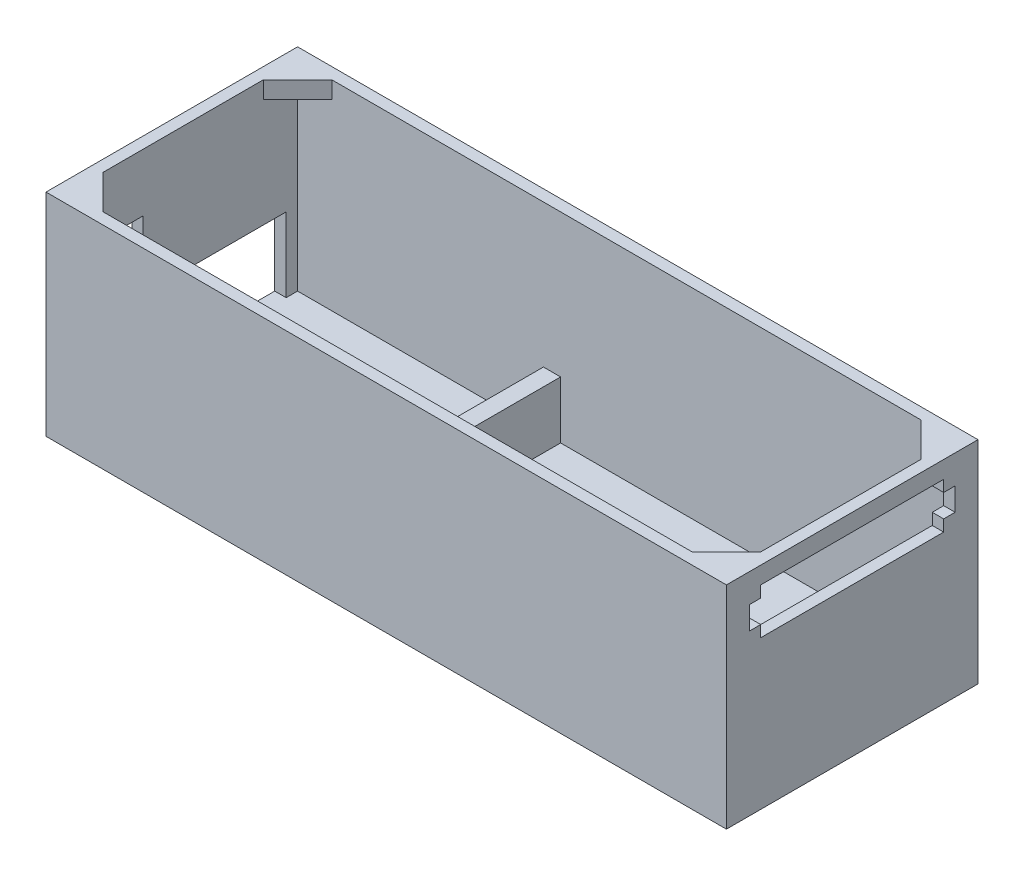
SolidWorks part; units mm, degrees
ref_plane "Plano frontal" through (0, 0, 0) normal (0, 0, 1) x (1, 0, 0)
ref_plane "Plano superior" through (0, 0, 0) normal (0, 1, 0) x (1, 0, 0)
ref_plane "Plano direito" through (0, 0, 0) normal (1, 0, 0) x (0, 0, -1)
sketch "Esboço1" plane through (0, 0, 0) normal (0, 1, 0) x (1, 0, 0)
  line L1 (-59.5, 22) -> (59.5, 22)
  line L2 (-59.5, 22) -> (-59.5, -22)
  line L3 (-59.5, -22) -> (59.5, -22)
  line L4 (59.5, 22) -> (59.5, -22)
  line L5 (-59.5, 22) -> (59.5, -22) construction
  line L6 (-59.5, -22) -> (59.5, 22) construction
  point P0 (0, 0)
  dimension "D1" = 44
  dimension "D2" = 119
extrude "Ressalto-extrusão2" add sketch "Esboço1" along normal blind 2
sketch "Esboço2" plane through (0, 2, 0) normal (0, 1, 0) x (1, 0, 0)
  line L1 (-59.5, -22) -> (59.5, -22)
  line L2 (-59.5, -22) -> (-59.5, 22)
  line L3 (-59.5, 22) -> (59.5, 22)
  line L4 (59.5, -22) -> (59.5, 22)
  line L5 (-59.5, -22) -> (59.5, 22) construction
  line L6 (-59.5, 22) -> (59.5, -22) construction
  line L7 (-57.5, -20) -> (57.5, -20)
  line L8 (-57.5, -20) -> (-57.5, 20)
  line L9 (-57.5, 20) -> (57.5, 20)
  line L10 (57.5, -20) -> (57.5, 20)
  line L11 (-57.5, -20) -> (57.5, 20) construction
  line L12 (-57.5, 20) -> (57.5, -20) construction
  point P0 (0, 0)
  point P7 (0, 0)
  dimension "D1" = 2
  dimension "D2" = 2
extrude "Ressalto-extrusão3" add sketch "Esboço2" along normal blind 35
sketch "Esboço3" plane through (0, 2, 0) normal (0, 1, 0) x (1, 0, 0)
  line L0 (57.5, 20) -> (-57.5, 20) construction
  line L1 (-57.5, -20) -> (-14.5, -20)
  line L2 (-57.5, -20) -> (-57.5, -1)
  line L3 (-57.5, -1) -> (-14.5, -1)
  line L4 (-14.5, -20) -> (-14.5, -1)
  line L5 (-57.5, -15) -> (-46.5, -15)
  line L6 (-57.5, -15) -> (-57.5, -6)
  line L7 (-57.5, -6) -> (-46.5, -6)
  line L8 (-46.5, -15) -> (-46.5, -6)
  line L9 (-14.5, -20) -> (-11.5, -20)
  line L10 (-14.5, -20) -> (-14.5, 20)
  line L11 (-14.5, 20) -> (-11.5, 20)
  line L12 (-11.5, -20) -> (-11.5, 20)
  line M11 (57.5, 20) -> (-57.5, 20)
  line M12 (-57.5, 20) -> (-57.5, -20)
  line M13 (-57.5, -20) -> (57.5, -20)
  dimension "D1" = 43
  dimension "D2" = 19
  dimension "D3" = 9
  dimension "D4" = 11
  dimension "D5" = 5
  dimension "D6" = 3
extrude "Ressalto-extrusão5" add sketch "Esboço3" along normal blind 3 contours L8 L5 L2 L4 L3 L7 M13 M12 | L12 L10 L4 M13 M11
sketch "Esboço5" plane through (0, 5, 0) normal (0, 1, 0) x (1, 0, 0)
  line L0 (-11.5, 20) -> (-14.5, 20) construction
  line L1 (-14.5, 20) -> (-11.5, 20)
  line L2 (-14.5, 20) -> (-14.5, -20)
  line L3 (-14.5, -20) -> (-11.5, -20)
  line L4 (-11.5, 20) -> (-11.5, -20)
  line L5 (-14.5, -1) -> (-14.5, 20) construction
  line L6 (-11.5, -20) -> (57.5, -20) construction
  line L7 (-57.5, -20) -> (57.5, -20) construction
extrude "Ressalto-extrusão6" add sketch "Esboço5" along normal blind 7
sketch "Esboço8" plane through (-57.5, 0, 0) normal (1, 0, 0) x (0, 0, -1)
  line L0 (-22, 37) -> (-22, 0) construction
  line L1 (-15, 2) -> (-6, 2)
  line L2 (-15, 2) -> (-15, 6)
  line L3 (-15, 6) -> (-6, 6)
  line L4 (-6, 2) -> (-6, 6)
  line L5 (-22, 0) -> (22, 0) construction
  point P6 (-10.5, 2)
  dimension "D1" = 7
  dimension "D2" = 2
  dimension "D3" = 9
  dimension "D4" = 4
extrude "Corte-extrusão1" cut sketch "Esboço8" against normal blind 7
sketch "Esboço9" plane through (-57.5, 0, 0) normal (1, 0, 0) x (0, 0, -1)
  line L0 (22, 37) -> (22, 0) construction
  line L1 (18, 2) -> (1, 2)
  line L2 (18, 2) -> (18, 15)
  line L3 (18, 15) -> (1, 15)
  line L4 (1, 2) -> (1, 15)
  line L5 (-22, 0) -> (22, 0) construction
  dimension "D1" = 4
  dimension "D2" = 2
  dimension "D3" = 13
  dimension "D4" = 17
extrude "Corte-extrusão2" cut sketch "Esboço9" against normal blind 7 contours L2 L1 L4 L3
sketch "Esboço10" plane through (59.5, 0, 0) normal (1, 0, 0) x (0, 0, -1)
  line L0 (-22, 37) -> (22, 37) construction
  line L1 (-16, 26) -> (16, 26)
  line L2 (-16, 26) -> (-16, 28)
  line L3 (-16, 34) -> (16, 34)
  line L4 (16, 26) -> (16, 28)
  line L5 (-22, 37) -> (-22, 0) construction
  line L6 (16, 32) -> (18, 32)
  line L7 (-16, 32) -> (-18, 32)
  line L8 (-18, 32) -> (-18, 28)
  line L9 (-18, 28) -> (-16, 28)
  line L10 (16, 28) -> (18, 28)
  line L11 (18, 32) -> (18, 28)
  line L12 (16, 32) -> (16, 34)
  line L13 (-16, 32) -> (-16, 34)
  dimension "D1" = 8
  dimension "D2" = 32
  dimension "D3" = 3
  dimension "D4" = 6
  dimension "D5" = 2
  dimension "D6" = 4
  dimension "D7" = 2
  dimension "D8" = 2
extrude "Corte-extrusão5" cut sketch "Esboço10" against normal blind 7
sketch "Esboço11" plane through (0, 37, 0) normal (0, 1, 0) x (1, 0, 0)
  line L0 (-59.5, 22) -> (-59.5, 12)
  line L1 (-59.5, 22) -> (-59.5, -22) construction
  line L2 (-59.5, 12) -> (-49.5, 22)
  line L3 (59.5, 22) -> (-59.5, 22) construction
  line L4 (-49.5, 22) -> (-59.5, 22)
  dimension "D1" = 10
  dimension "D2" = 10
extrude "Ressalto-extrusão7" add sketch "Esboço11" against normal blind 3
mirror "Espelhar1" about plane through (0, 0, 0) normal (0, 0, 1) of "Ressalto-extrusão7"
mirror "Espelhar2" about plane through (0, 0, 0) normal (1, 0, 0) of "Ressalto-extrusão7"
mirror "Espelhar3" about plane through (0, 0, 0) normal (1, 0, 0) of "Espelhar1"
sketch "Esboço12" plane through (0, 12, 0) normal (0, 1, 0) x (1, 0, 0)
  line L0 (-14.5, 20) -> (-14.5, -20) construction
  line L1 (-14.5, -1.25) -> (-11.5, -1.25)
  line L2 (-14.5, -1.25) -> (-14.5, 1.75)
  line L3 (-14.5, 1.75) -> (-11.5, 1.75)
  line L4 (-11.5, -1.25) -> (-11.5, 1.75)
  line L5 (-11.5, -20) -> (-11.5, 20) construction
  line L6 (-14.5, -20) -> (-11.5, -20) construction
  dimension "D1" = 3
  dimension "D2" = 18.75
extrude "Corte-extrusão6" cut sketch "Esboço12" against normal blind 6
sketch "Esboço13" plane through (-59.5, 0, 0) normal (-1, 0, 0) x (0, 0, 1)
  line L0 (-18, 2) -> (-18, 15) construction
  line L1 (7, 23.4056) -> (13.5, 23.4056)
  line L2 (7, 23.4056) -> (7, 26.9056)
  line L3 (7, 26.9056) -> (13.5, 26.9056)
  line L4 (13.5, 23.4056) -> (13.5, 26.9056)
  dimension "D1" = 6.5
  dimension "D2" = 3.5
  dimension "D3" = 25
extrude "Corte-extrusão7" cut sketch "Esboço13" against normal blind 10
